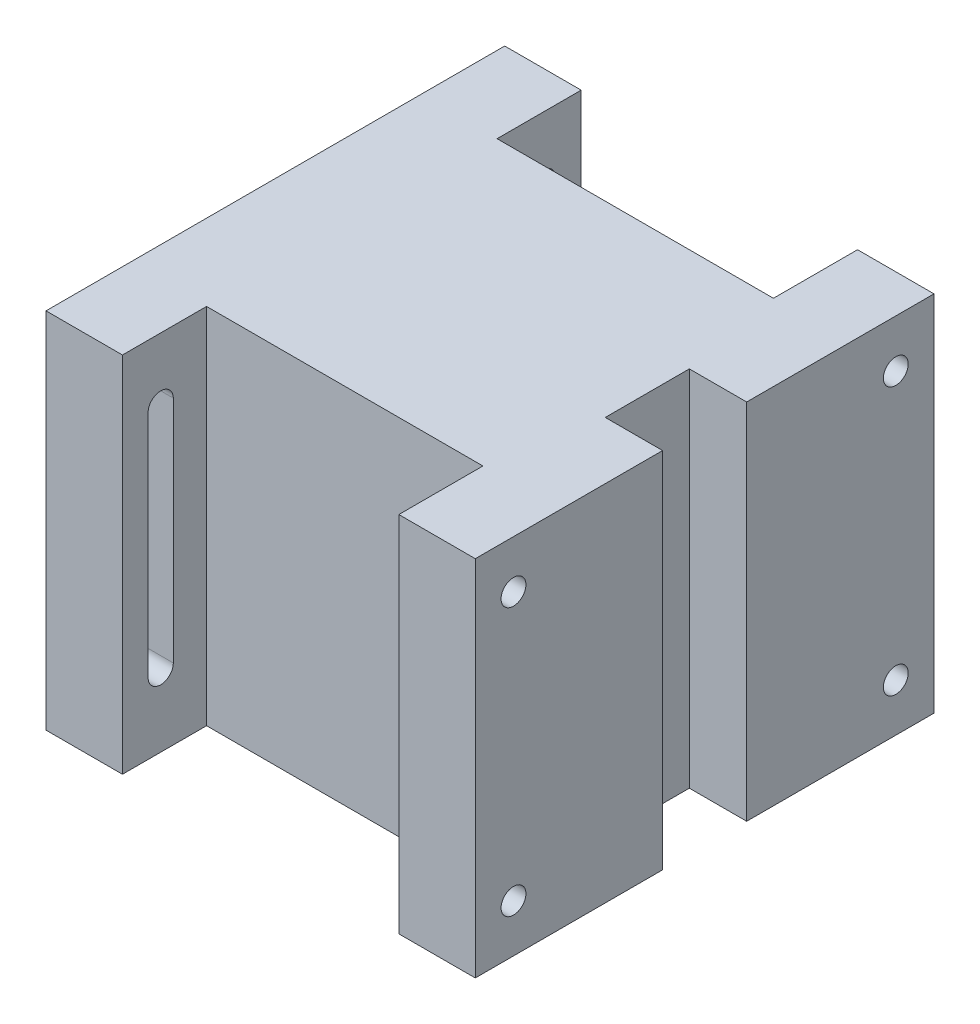
SolidWorks part; units mm, degrees
material "SKD11淬火HRC56-60"
ref_plane "前基準面" through (0, 0, 0) normal (0, 0, 1) x (1, 0, 0)
ref_plane "上基準面" through (0, 0, 0) normal (0, 1, 0) x (1, 0, 0)
ref_plane "右基準面" through (0, 0, 0) normal (1, 0, 0) x (0, 0, -1)
sketch "草图1" plane through (0, 0, 0) normal (0, 0, 1) x (1, 0, 0)
  line L1 (0, 0) -> (112.3, 0)
  line L2 (0, 0) -> (0, 95)
  line L3 (0, 95) -> (112.3, 95)
  line L4 (112.3, 0) -> (112.3, 95)
  dimension "D1" = 112.3
  dimension "D2" = 95
extrude "凸台-拉伸1" add sketch "草图1" along normal blind 120
sketch "草图2" plane through (0, 0, 0) normal (0, -1, 0) x (1, 0, 0)
  line L0 (0, 120) -> (112.3, 120) construction
  line L1 (92.3, 120) -> (20, 120)
  line L2 (92.3, 120) -> (92.3, 98)
  line L3 (92.3, 98) -> (20, 98)
  line L4 (20, 120) -> (20, 98)
  line L5 (0, 120) -> (0, 0) construction
  line L6 (112.3, 120) -> (112.3, 0) construction
  line L7 (0, 60) -> (112.3, 60) construction
  line L8 (20, 0) -> (20, 22)
  line L9 (92.3, 22) -> (20, 22)
  line L10 (92.3, 0) -> (92.3, 22)
  line L11 (92.3, 0) -> (20, 0)
  dimension "D1" = 22
  dimension "D2" = 20
  dimension "D3" = 20
extrude "切除-拉伸1" cut sketch "草图2" against normal through all
sketch "草图3" plane through (0, 0, 0) normal (-1, 0, 0) x (0, 0, 1)
  line L0 (110, 18.577) -> (110, 78.577) construction
  line L1 (106.7, 18.577) -> (106.7, 78.577)
  line L2 (113.3, 18.577) -> (113.3, 78.577)
  line L3 (60, 0) -> (60, 95) construction
  line L4 (120, 0) -> (0, 0) construction
  line L5 (120, 95) -> (0, 95) construction
  line L6 (10, 18.577) -> (10, 78.577) construction
  line L7 (13.3, 18.577) -> (13.3, 78.577)
  line L8 (6.7, 18.577) -> (6.7, 78.577)
  line L9 (60, 47.5) -> (141.0983, 47.5) construction
  arc A0 (106.7, 18.577) -> (113.3, 18.577) centre (110, 18.577) ccw
  arc A1 (113.3, 78.577) -> (106.7, 78.577) centre (110, 78.577) ccw
  arc A2 (13.3, 18.577) -> (6.7, 18.577) centre (10, 18.577) cw
  arc A3 (6.7, 78.577) -> (13.3, 78.577) centre (10, 78.577) cw
  point P2 (110, 48.577)
  point P15 (10, 48.577)
  dimension "D1" = 6.6
  dimension "D2" = 60
  dimension "D3" = 100
extrude "切除-拉伸2" cut sketch "草图3" against normal blind 25
sketch "草图4" plane through (112.3, 0, 0) normal (1, 0, 0) x (0, 0, -1)
  line L0 (-60, 95) -> (-60, 0) construction
  line L1 (-120, 95) -> (0, 95) construction
  line L2 (-120, 0) -> (0, 0) construction
  line L3 (-120, 47.5) -> (0, 47.5) construction
  line L4 (-120, 0) -> (-120, 95) construction
  line L5 (0, 0) -> (0, 95) construction
  circle A0 centre (-110, 82.5) radius 3.25
  circle A1 centre (-10, 82.5) radius 3.25
  circle A2 centre (-10, 12.5) radius 3.25
  circle A3 centre (-110, 12.5) radius 3.25
  dimension "D1" = 6.5
  dimension "D2" = 70
  dimension "D3" = 100
extrude "切除-拉伸3" cut sketch "草图4" against normal blind 25
sketch "草图6" plane through (112.3, 0, 0) normal (1, 0, 0) x (0, 0, -1)
  line L0 (-120, 95) -> (0, 95) construction
  line L1 (-49, 95) -> (-71, 95)
  line L2 (-49, 95) -> (-49, 0)
  line L3 (-49, 0) -> (-71, 0)
  line L4 (-71, 95) -> (-71, 0)
  line L5 (-120, 0) -> (0, 0) construction
  line L6 (-60, -1.8558) -> (-60, 95) construction
  dimension "D1" = 22
extrude "切除-拉伸4" cut sketch "草图6" against normal blind 15
